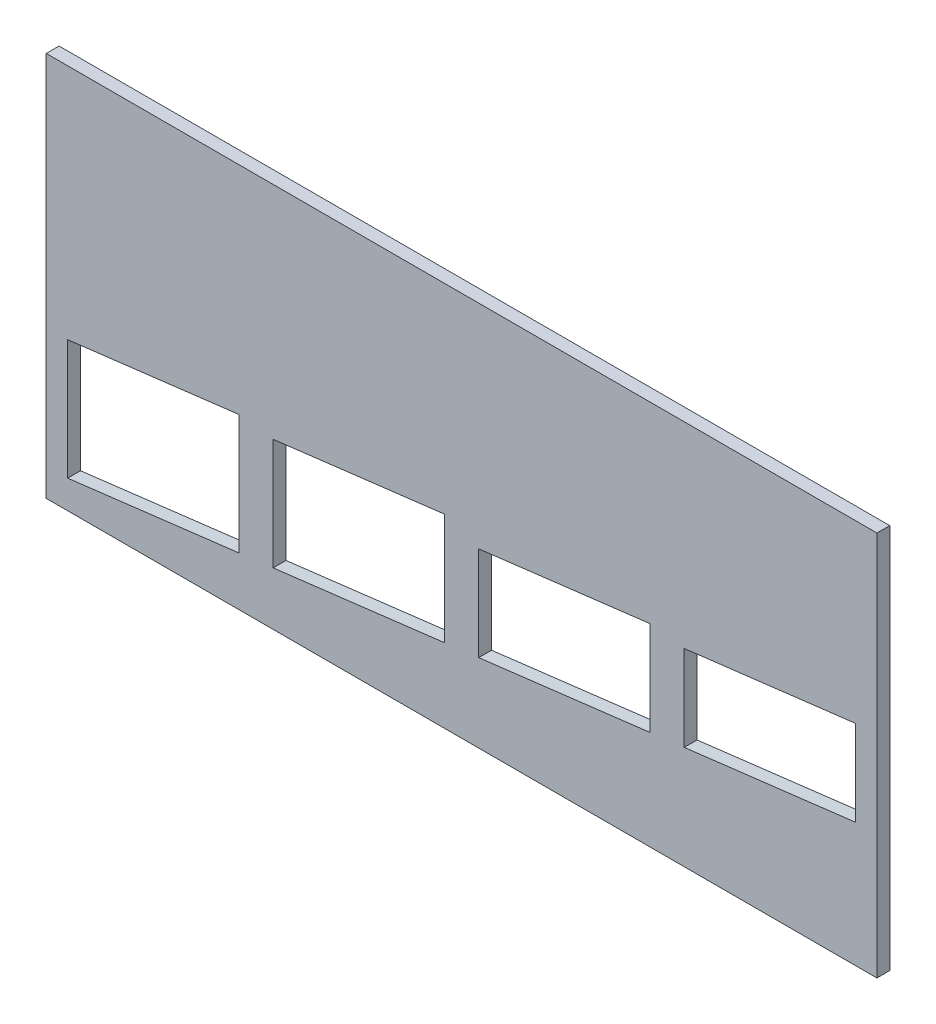
SolidWorks part; units mm, degrees
ref_plane "前基準面" through (0, 0, 0) normal (0, 0, 1) x (1, 0, 0)
ref_plane "上基準面" through (0, 0, 0) normal (0, 1, 0) x (1, 0, 0)
ref_plane "右基準面" through (0, 0, 0) normal (1, 0, 0) x (0, 0, -1)
sketch "草圖1" plane through (0, 0, 0) normal (0, 0, 1) x (1, 0, 0)
  line L1 (-98.5, 45.0091) -> (95.5, 45.0091)
  line L3 (-98.5, -44.9909) -> (95.5, -44.9909)
  line L4 (95.5, 45.0091) -> (95.5, -44.9909)
  line L6 (-98.5, 45.0091) -> (95.5, 45.0091)
  line L7 (-93.5, -38.3909) -> (-53.5, -33.5178)
  line L8 (-93.5, -38.3909) -> (-93.5, -10.3909)
  line L9 (-53.5, -33.5178) -> (-53.5, -5.5178)
  line L10 (-93.5, -10.3909) -> (-53.5, -5.5178)
  line L11 (-45.5, -32.5431) -> (-5.5, -27.6701)
  line L12 (-45.5, -32.5431) -> (-45.5, -6.5431)
  line L13 (-5.5, -27.6701) -> (-5.5, -1.6701)
  line L14 (-45.5, -6.5431) -> (-5.5, -1.6701)
  line L15 (2.5, -26.6954) -> (42.5, -21.8223)
  line L16 (2.5, -26.6954) -> (2.5, -4.6954)
  line L17 (42.5, -21.8223) -> (42.5, 0.1777)
  line L18 (2.5, -4.6954) -> (42.5, 0.1777)
  line L19 (50.5, -20.8477) -> (90.5, -15.9909)
  line L20 (50.5, -20.8477) -> (50.5, -0.8477)
  line L21 (90.5, -15.9909) -> (90.5, 4.0091)
  line L22 (50.5, -0.8477) -> (90.5, 4.0091)
  line L23 (-98.5, 45.0091) -> (-98.5, -44.9909)
  line L24 (-98.5, -44.9909) -> (95.5, -44.9909)
  line L25 (95.5, 45.0091) -> (95.5, -44.9909)
  point P0 (0, 0)
  dimension "D1" = 194
  dimension "D2" = 90
  dimension "D3" = 6.6
  dimension "D4" = 29
  dimension "D5" = 5
  dimension "D6" = 8
  dimension "D7" = 40
  dimension "D8" = 40
  dimension "D9" = 40
  dimension "D10" = 40
  dimension "D11" = 8
  dimension "D12" = 8
  dimension "D13" = 28
  dimension "D14" = 26
  dimension "D15" = 22
  dimension "D16" = 20
extrude "填料-伸長1" add sketch "草圖1" along normal blind 3 contours L1 L23 L3 L4 L20 L22 L21 L19 L16 L18 L17 L15 L12 L14 L13 L11 L8 L10 L9 L7
